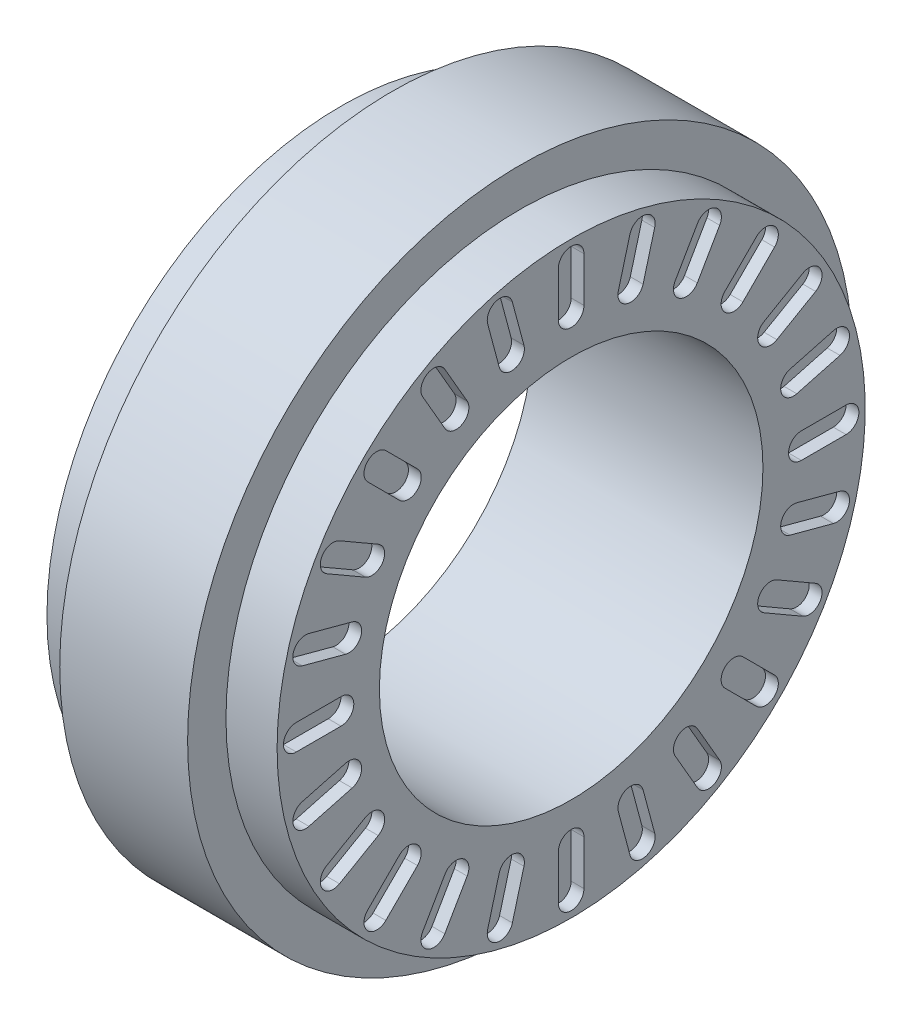
SolidWorks part; units mm, degrees
ref_plane "Front Plane" through (0, 0, 0) normal (0, 0, 1) x (1, 0, 0)
ref_plane "Top Plane" through (0, 0, 0) normal (0, 1, 0) x (1, 0, 0)
ref_plane "Right Plane" through (0, 0, 0) normal (1, 0, 0) x (0, 0, -1)
sketch "Sketch3" plane through (0, 0, 0) normal (0, 1, 0) x (1, 0, 0)
  line L0 (0, 15) -> (0, 26)
  line L1 (0, 26) -> (5, 26)
  line L2 (5, 26) -> (5, 23)
  line L3 (5, 23) -> (9, 23)
  line L4 (9, 23) -> (9, 15)
  line L5 (9, 15) -> (0, 15)
  line L6 (0, 0) -> (9.5782, 0) construction
  dimension "D1" = 23
  dimension "D2" = 15
  dimension "D3" = 5
  dimension "D4" = 4
  dimension "D5" = 3
revolve "Revolve1" add sketch "Sketch3" angle 360 about L6
mirror "Mirror3" about plane through (0, 0, -15) normal (1, 0, 0) of "Revolve1"
sketch "Sketch4" plane through (9, 0, 0) normal (1, 0, 0) x (0, 0, -1)
  line L0 (-1, 21.5) -> (-1, 18)
  line L1 (1, 21.5) -> (1, 18)
  arc A0 (-1, 21.5) -> (1, 21.5) centre (0, 21.5) cw
  arc A1 (-1, 18) -> (1, 18) centre (0, 18) ccw
  dimension "D1" = 3.5
  dimension "D3" = 21.5
  dimension "D2" = 2
extrude "Cut-Extrude1" cut sketch "Sketch4" against normal blind 1
pattern_circular "CirPattern1" count 24 over 360 about axis through (0, 0, 0) along (1, 0, 0) of "Cut-Extrude1"
mirror "Mirror4" about plane through (0, 0, 0) normal (1, 0, 0) of "CirPattern1", "Cut-Extrude1"
